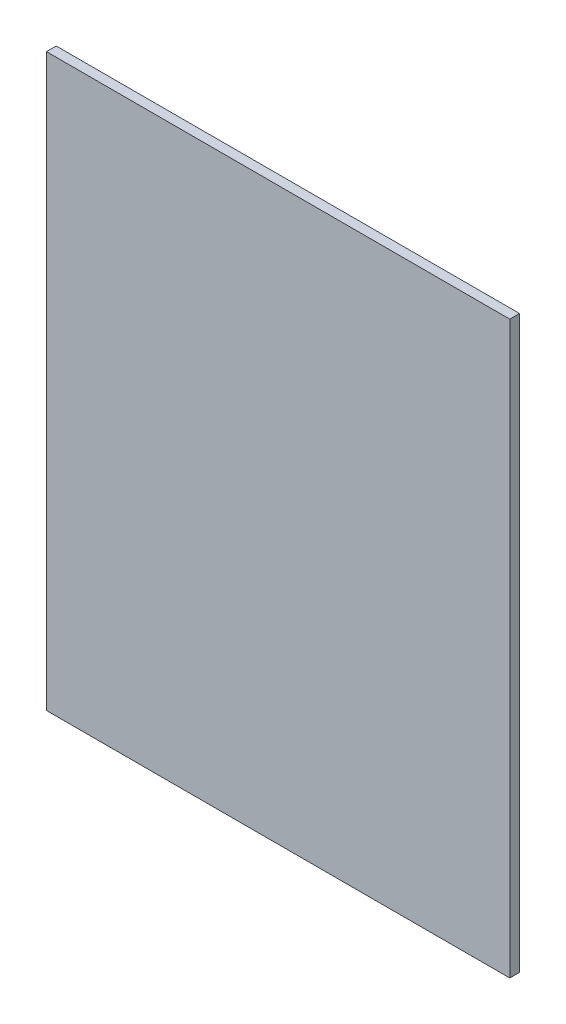
SolidWorks part; units mm, degrees
ref_plane "Front Plane" through (0, 0, 0) normal (0, 0, 1) x (1, 0, 0)
ref_plane "Top Plane" through (0, 0, 0) normal (0, 1, 0) x (1, 0, 0)
ref_plane "Right Plane" through (0, 0, 0) normal (1, 0, 0) x (0, 0, -1)
sketch "Sketch1" plane through (0, 0, 0) normal (0, 0, 1) x (1, 0, 0)
  line L1 (-190, -234) -> (190, -234)
  line L2 (-190, -234) -> (-190, 234)
  line L3 (-190, 234) -> (190, 234)
  line L4 (190, -234) -> (190, 234)
  line L5 (-190, -234) -> (190, 234) construction
  line L6 (-190, 234) -> (190, -234) construction
  point P0 (0, 0)
  dimension "D1" = 468
  dimension "D2" = 380
extrude "Boss-Extrude1" add sketch "Sketch1" along normal blind 8
